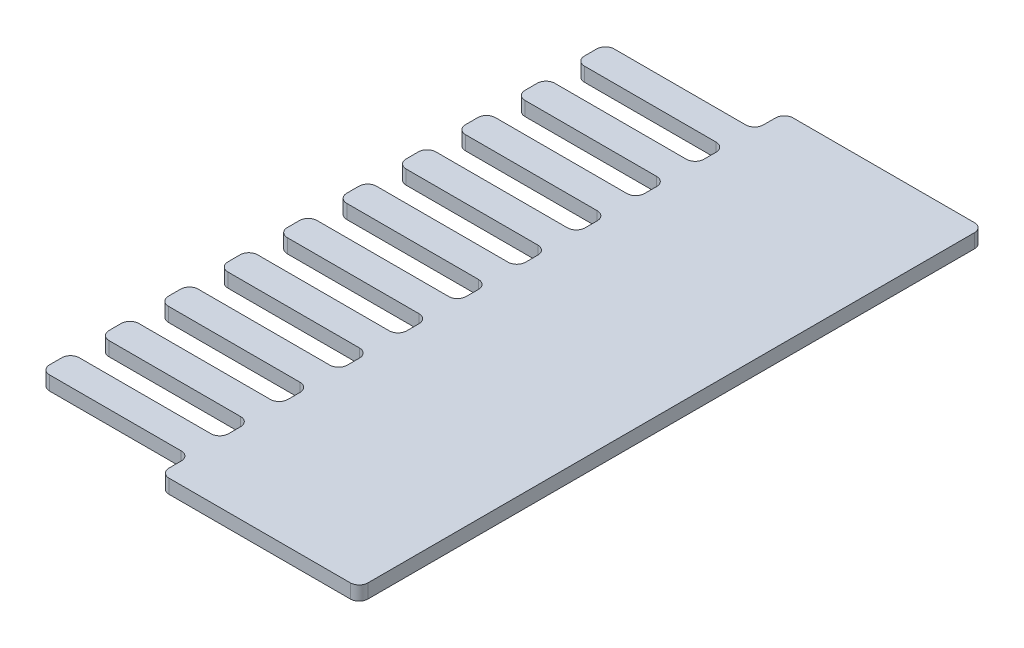
SolidWorks part; units mm, degrees
ref_plane "Front Plane" through (0, 0, 0) normal (0, 0, 1) x (1, 0, 0)
ref_plane "Top Plane" through (0, 0, 0) normal (0, 1, 0) x (1, 0, 0)
ref_plane "Right Plane" through (0, 0, 0) normal (1, 0, 0) x (0, 0, -1)
sketch "Sketch1" plane through (0, 0, 0) normal (0, 1, 0) x (1, 0, 0)
  line L0 (-0.75, 2.54) -> (-12, 2.54)
  line L2 (0, 1.79) -> (0, 0.75)
  line L5 (-12.75, 3.81) -> (0, 3.81) construction
  line L7 (-12.75, 3.29) -> (-12.75, 4.33)
  line L8 (-12, 5.08) -> (-0.75, 5.08)
  line L12 (0, 6.87) -> (0, 5.83)
  line L17 (-0.75, 7.62) -> (-12, 7.62)
  line L22 (-12.75, 8.37) -> (-12.75, 9.41)
  line L27 (-12, 10.16) -> (-0.75, 10.16)
  line L32 (0, 11.95) -> (0, 10.91)
  line L37 (-0.75, 12.7) -> (-12, 12.7)
  line L42 (-12.75, 13.45) -> (-12.75, 14.49)
  line L47 (-12, 15.24) -> (-0.75, 15.24)
  line L52 (0, 17.03) -> (0, 15.99)
  line L53 (0, 51.55) -> (0, 52.59)
  line L54 (0.75, 53.34) -> (16.25, 53.34)
  line L55 (17, 52.59) -> (17, 0.75)
  line L56 (16.25, 0) -> (0.75, 0)
  line L57 (-0.75, 17.78) -> (-12, 17.78)
  line L58 (-12.75, 18.53) -> (-12.75, 19.57)
  line L59 (-12, 20.32) -> (-0.75, 20.32)
  line L60 (0, 22.11) -> (0, 21.07)
  line L61 (-0.75, 22.86) -> (-12, 22.86)
  line L62 (-12.75, 23.61) -> (-12.75, 24.65)
  line L63 (-12, 25.4) -> (-0.75, 25.4)
  line L64 (0, 27.19) -> (0, 26.15)
  line L65 (-0.75, 27.94) -> (-12, 27.94)
  line L66 (-12.75, 28.69) -> (-12.75, 29.73)
  line L67 (-12, 30.48) -> (-0.75, 30.48)
  line L68 (0, 32.27) -> (0, 31.23)
  line L69 (-0.75, 33.02) -> (-12, 33.02)
  line L70 (-12.75, 33.77) -> (-12.75, 34.81)
  line L71 (-12, 35.56) -> (-0.75, 35.56)
  line L72 (0, 37.35) -> (0, 36.31)
  line L73 (-0.75, 38.1) -> (-12, 38.1)
  line L74 (-12.75, 38.85) -> (-12.75, 39.89)
  line L75 (-12, 40.64) -> (-0.75, 40.64)
  line L76 (0, 42.43) -> (0, 41.39)
  line L77 (-0.75, 43.18) -> (-12, 43.18)
  line L78 (-12.75, 43.93) -> (-12.75, 44.97)
  line L79 (-12, 45.72) -> (-0.75, 45.72)
  line L80 (0, 47.51) -> (0, 46.47)
  line L81 (-0.75, 48.26) -> (-12, 48.26)
  line L82 (-12.75, 49.01) -> (-12.75, 50.05)
  line L83 (-12, 50.8) -> (-0.75, 50.8)
  arc A0 (-0.75, 5.08) -> (0, 5.83) centre (-0.75, 5.83) ccw
  arc A1 (-12.75, 4.33) -> (-12, 5.08) centre (-12, 4.33) cw
  arc A2 (-12, 2.54) -> (-12.75, 3.29) centre (-12, 3.29) cw
  arc A3 (0, 0.75) -> (0.75, 0) centre (0.75, 0.75) ccw
  arc A4 (-0.75, 2.54) -> (0, 1.79) centre (-0.75, 1.79) cw
  arc A5 (17, 0.75) -> (16.25, 0) centre (16.25, 0.75) cw
  arc A6 (-0.75, 7.62) -> (0, 6.87) centre (-0.75, 6.87) cw
  arc A7 (-12, 7.62) -> (-12.75, 8.37) centre (-12, 8.37) cw
  arc A8 (-12.75, 9.41) -> (-12, 10.16) centre (-12, 9.41) cw
  arc A9 (-0.75, 10.16) -> (0, 10.91) centre (-0.75, 10.91) ccw
  arc A10 (-0.75, 12.7) -> (0, 11.95) centre (-0.75, 11.95) cw
  arc A11 (-12, 12.7) -> (-12.75, 13.45) centre (-12, 13.45) cw
  arc A12 (-12.75, 14.49) -> (-12, 15.24) centre (-12, 14.49) cw
  arc A13 (-0.75, 15.24) -> (0, 15.99) centre (-0.75, 15.99) ccw
  arc A14 (-0.75, 17.78) -> (0, 17.03) centre (-0.75, 17.03) cw
  arc A15 (-12, 17.78) -> (-12.75, 18.53) centre (-12, 18.53) cw
  arc A16 (-12.75, 19.57) -> (-12, 20.32) centre (-12, 19.57) cw
  arc A17 (-0.75, 20.32) -> (0, 21.07) centre (-0.75, 21.07) ccw
  arc A18 (-0.75, 22.86) -> (0, 22.11) centre (-0.75, 22.11) cw
  arc A19 (-12, 22.86) -> (-12.75, 23.61) centre (-12, 23.61) cw
  arc A20 (-12.75, 24.65) -> (-12, 25.4) centre (-12, 24.65) cw
  arc A21 (-0.75, 25.4) -> (0, 26.15) centre (-0.75, 26.15) ccw
  arc A22 (-0.75, 27.94) -> (0, 27.19) centre (-0.75, 27.19) cw
  arc A23 (-12, 27.94) -> (-12.75, 28.69) centre (-12, 28.69) cw
  arc A24 (-12.75, 29.73) -> (-12, 30.48) centre (-12, 29.73) cw
  arc A25 (-0.75, 30.48) -> (0, 31.23) centre (-0.75, 31.23) ccw
  arc A26 (-0.75, 33.02) -> (0, 32.27) centre (-0.75, 32.27) cw
  arc A27 (-12, 33.02) -> (-12.75, 33.77) centre (-12, 33.77) cw
  arc A28 (-12.75, 34.81) -> (-12, 35.56) centre (-12, 34.81) cw
  arc A29 (-0.75, 35.56) -> (0, 36.31) centre (-0.75, 36.31) ccw
  arc A30 (-0.75, 38.1) -> (0, 37.35) centre (-0.75, 37.35) cw
  arc A31 (-12, 38.1) -> (-12.75, 38.85) centre (-12, 38.85) cw
  arc A32 (-12.75, 39.89) -> (-12, 40.64) centre (-12, 39.89) cw
  arc A33 (-0.75, 40.64) -> (0, 41.39) centre (-0.75, 41.39) ccw
  arc A34 (-0.75, 43.18) -> (0, 42.43) centre (-0.75, 42.43) cw
  arc A35 (-12, 43.18) -> (-12.75, 43.93) centre (-12, 43.93) cw
  arc A36 (-12.75, 44.97) -> (-12, 45.72) centre (-12, 44.97) cw
  arc A37 (-0.75, 45.72) -> (0, 46.47) centre (-0.75, 46.47) ccw
  arc A38 (-0.75, 48.26) -> (0, 47.51) centre (-0.75, 47.51) cw
  arc A39 (-12, 48.26) -> (-12.75, 49.01) centre (-12, 49.01) cw
  arc A40 (-12.75, 50.05) -> (-12, 50.8) centre (-12, 50.05) cw
  arc A41 (-0.75, 50.8) -> (0, 51.55) centre (-0.75, 51.55) ccw
  arc A42 (0, 52.59) -> (0.75, 53.34) centre (0.75, 52.59) cw
  arc A43 (16.25, 53.34) -> (17, 52.59) centre (16.25, 52.59) cw
  point P0 (0, 0)
  point P27 (0, 5.08)
  point P48 (-12.75, 5.08)
  point P69 (-12.75, 2.54)
  point P78 (0, 0)
  point P81 (0, 2.54)
  point P84 (17, 0)
  dimension "D6" = 0.75
  dimension "D7" = 0.75
  dimension "D8" = 0.75
  dimension "D9" = 0.75
  dimension "D1" = 2.54
  dimension "D2" = 12
  dimension "D3" = 10
  dimension "D4" = 2.54
  dimension "D5" = 17
  dimension "D10" = 5.08
extrude "Boss-Extrude1" add sketch "Sketch1" along normal blind 1.2
